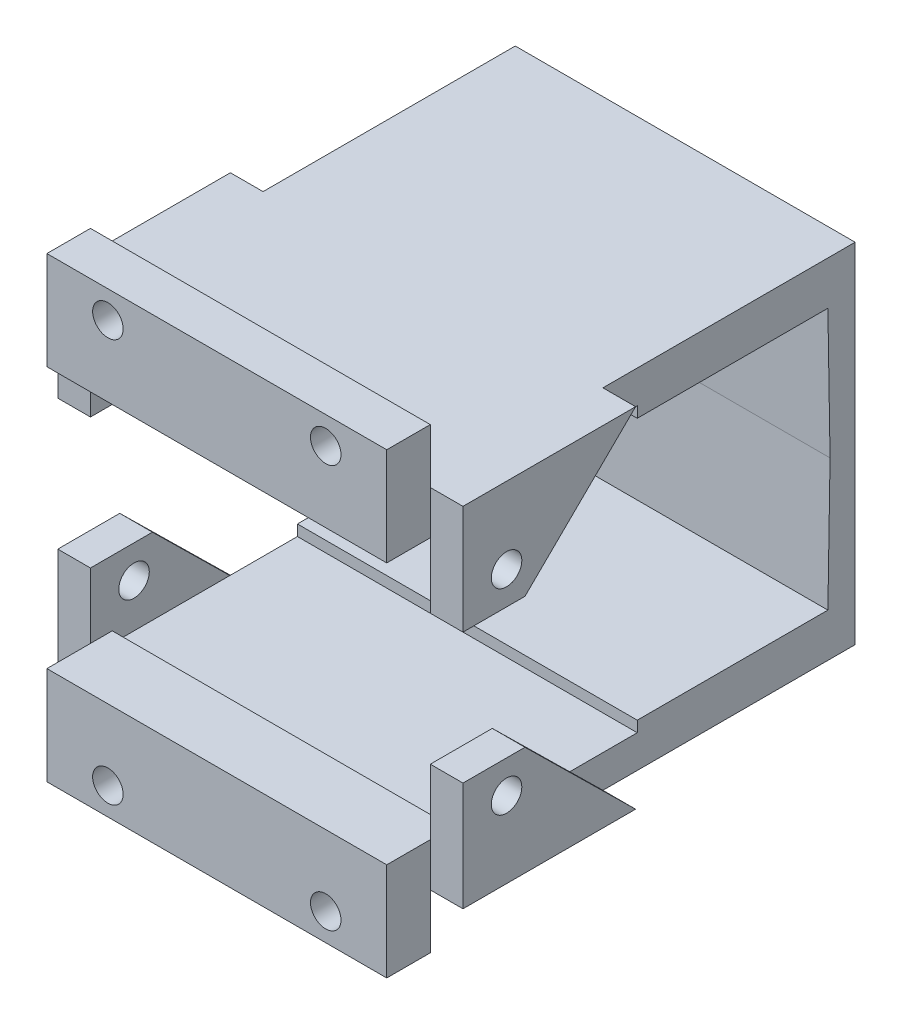
SolidWorks part; units mm, degrees
ref_plane "前视基准面" through (0, 0, 0) normal (0, 0, 1) x (1, 0, 0)
ref_plane "上视基准面" through (0, 0, 0) normal (0, 1, 0) x (1, 0, 0)
ref_plane "右视基准面" through (0, 0, 0) normal (1, 0, 0) x (0, 0, -1)
sketch "草图1" plane through (0, 0, 0) normal (0, 0, 1) x (1, 0, 0)
  line L0 (-15.6, 12) -> (15.6, 12)
  line L3 (-15.6, -12) -> (15.6, -12)
  line L4 (15.6, 12) -> (15.6, -12)
  line L5 (-15.6, 12) -> (-15.6, -12)
extrude "凸台-拉伸1" add sketch "草图1" along normal blind 2 and the other way blind 1
sketch "草图2" plane through (0, 0, 2) normal (0, 0, 1) x (1, 0, 0)
  line L1 (15.6, 12) -> (-15.6, 12)
  line L2 (15.6, 12) -> (15.6, 16)
  line L3 (15.6, 16) -> (-15.6, 16)
  line L4 (-15.6, 12) -> (-15.6, 16)
  line L5 (15.6, -16) -> (-15.6, -16)
  line L6 (-15.6, -12) -> (-15.6, -16)
  line L7 (15.6, -12) -> (-15.6, -12)
  line L8 (15.6, -12) -> (15.6, -16)
  dimension "D1" = 4
extrude "凸台-拉伸2" add sketch "草图2" along normal blind 36 and the other way blind 3
sketch "草图3" plane through (-15.6, 0, 0) normal (-1, 0, 0) x (0, 0, 1)
  line L0 (2, 12) -> (2, -12) construction
  line L1 (2, 12) -> (38, 12) construction
  line L3 (38, 16) -> (31, 16)
  line L4 (38, 16) -> (38, 6)
  line L5 (38, 6) -> (32.3107, 6)
  line L7 (32.3107, 6) -> (22.1529, 16)
  line L8 (-1, 16) -> (38, 16) construction
  line L9 (22.1529, 16) -> (31, 16)
  line L13 (38, -16) -> (38, -6)
  line L14 (38, -16) -> (31, -16)
  line L15 (22.1529, -16) -> (31, -16)
  line L16 (32.3107, -6) -> (22.1529, -16)
  line L17 (38, -6) -> (32.3107, -6)
  circle A0 centre (34, 9) radius 1.4
  circle A1 centre (34, -9) radius 1.4
  dimension "D1" = 32
  dimension "D2" = 3
  dimension "D3" = 10
  dimension "D4" = 7
extrude "凸台-拉伸3" add sketch "草图3" along normal blind 3
sketch "草图4" plane through (0, 0, -1) normal (0, 0, -1) x (-1, 0, 0)
  line L0 (15.6, -12) -> (15.6, -16) construction
  line L1 (15.6, -16) -> (-15.6, -16) construction
  circle A0 centre (13.6, -14) radius 1.4
  circle A1 centre (13.6, 14) radius 1.4
  circle A2 centre (-13.6, -14) radius 1.4
  circle A3 centre (-13.6, 14) radius 1.4
  dimension "D1" = 2
  dimension "D2" = 2
extrude "切除-拉伸1" cut sketch "草图4" against normal blind 8
mirror "镜向1" about plane through (0, 0, 0) normal (1, 0, 0) of "凸台-拉伸3"
sketch "草图5" plane through (-15.6, 0, 0) normal (-1, 0, 0) x (0, 0, 1)
  line L0 (2, 12) -> (26.216, 12) construction
  line L1 (19, 12) -> (36, 12)
  line L2 (19, 12) -> (19, 13)
  line L3 (19, 13) -> (36, 13)
  line L4 (36, 12) -> (36, 13)
  line L5 (2, 12) -> (2, -12) construction
  line L7 (19, -12) -> (19, -13)
  line L8 (19, -12) -> (36, -12)
  line L9 (19, -13) -> (36, -13)
  line L10 (36, -12) -> (36, -13)
  dimension "D1" = 17
  dimension "D2" = 34
  dimension "D3" = 1
extrude "切除-拉伸2" cut sketch "草图5" against normal blind 31.2
sketch "草图6" plane through (-15.6, 0, 0) normal (-1, 0, 0) x (0, 0, 1)
  line L0 (3.0082, 0) -> (2, 0)
  line L1 (2, 12) -> (1.5, 12)
  line L2 (2, 12) -> (2, -12)
  line L3 (2, -12) -> (1.5, -12)
  line L6 (1.3, 0) -> (1.5, 12)
  line L7 (1.3, 0) -> (1.5, -12)
  line M17 (2, -12) -> (2, 12)
  dimension "D1" = 0.5
extrude "切除-拉伸3" cut sketch "草图6" against normal blind 31.2 contours L6 L7 L3 L1 M17
sketch "草图7" plane through (0, 0, 38) normal (0, 0, 1) x (1, 0, 0)
  line L0 (18.6, 16) -> (-18.6, 16) construction
  line L1 (-15.6, 12) -> (15.6, 12)
  line L2 (-15.6, 12) -> (-15.6, 16)
  line L4 (15.6, 12) -> (15.6, 16)
  line L6 (15.6, 16) -> (15.6, 21)
  line L8 (-15.6, 16) -> (-15.6, 21)
  line L9 (-15.6, 21) -> (15.6, 21)
  line L11 (-15.6, -16) -> (-15.6, -21)
  line L12 (-15.6, -12) -> (-15.6, -16)
  line L13 (-15.6, -12) -> (15.6, -12)
  line L14 (15.6, -12) -> (15.6, -16)
  line L15 (15.6, -16) -> (15.6, -21)
  line L16 (-15.6, -21) -> (15.6, -21)
  circle A0 centre (-10, 18.5) radius 1.4
  circle A1 centre (10, 18.5) radius 1.4
  circle A2 centre (10, -18.5) radius 1.4
  circle A3 centre (-10, -18.5) radius 1.4
  dimension "D1" = 5
extrude "凸台-拉伸4" add sketch "草图7" along normal blind 4
